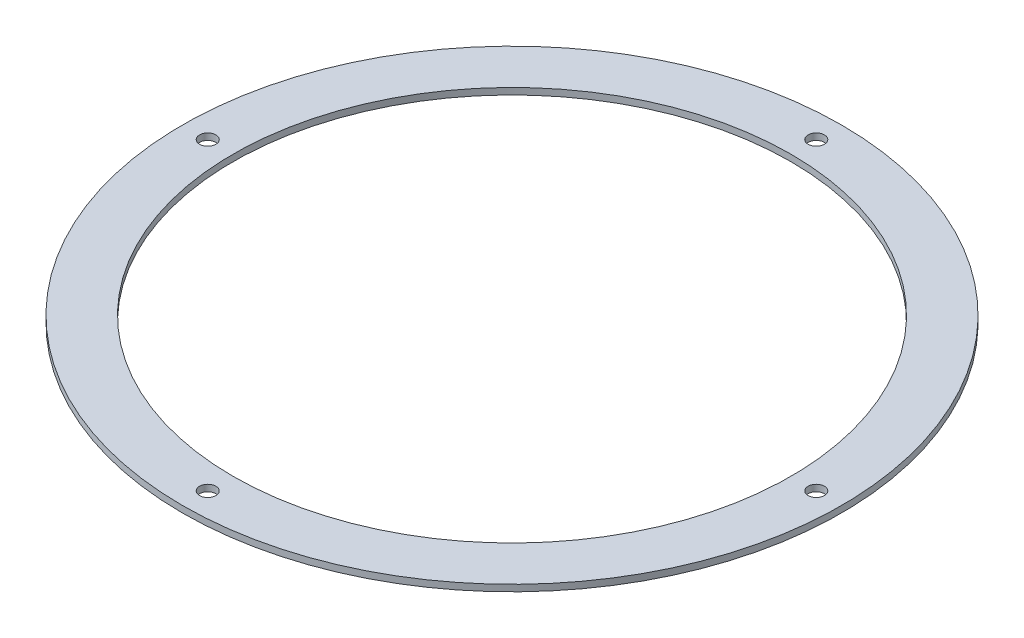
SolidWorks part; units mm, degrees
ref_plane "前视基准面" through (0, 0, 0) normal (0, 0, 1) x (1, 0, 0)
ref_plane "上视基准面" through (0, 0, 0) normal (0, 1, 0) x (1, 0, 0)
ref_plane "右视基准面" through (0, 0, 0) normal (1, 0, 0) x (0, 0, -1)
other "Configuration Table"
sketch "草图1" plane through (0, 0, 0) normal (0, 1, 0) x (1, 0, 0)
  line L0 (0, 0) -> (0, 101)
  line L1 (0, 85.5) -> (0, 72.5)
  line L2 (0, 85.5) -> (0, 101)
  circle A0 centre (0, 0) radius 72.5
  circle A1 centre (0, 0) radius 85.5
  circle A2 centre (0, 0) radius 101
  circle A3 centre (0, 79) radius 2.5
  circle A4 centre (79, 0) radius 2.5
  circle A5 centre (0, -79) radius 2.5
  circle A6 centre (-79, 0) radius 2.5
  circle A7 centre (0, 93.25) radius 2.5
  circle A8 centre (93.25, 0) radius 2.5
  circle A9 centre (0, -93.25) radius 2.5
  circle A10 centre (-93.25, 0) radius 2.5
  point P20 (0, 0)
  point P29 (0, 0)
  dimension "D1" = 145
  dimension "D3" = 202
  dimension "D4" = 5
  dimension "D5" = 5
  dimension "D2" = 13
extrude "凸台-拉伸2" add sketch "草图1" along normal blind 2
